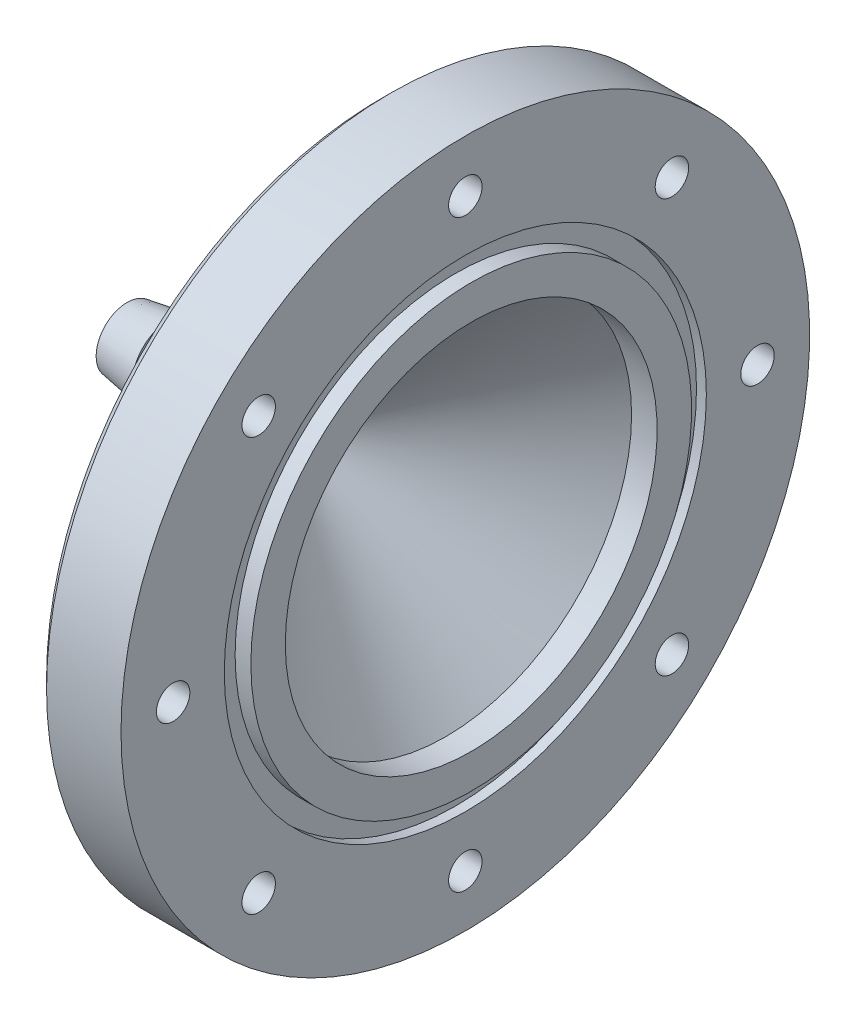
SolidWorks part; units mm, degrees
ref_plane "Front Plane" through (0, 0, 0) normal (0, 0, 1) x (1, 0, 0)
ref_plane "Top Plane" through (0, 0, 0) normal (0, 1, 0) x (1, 0, 0)
ref_plane "Right Plane" through (0, 0, 0) normal (1, 0, 0) x (0, 0, -1)
sketch "Sketch1" plane through (0, 0, 0) normal (0, 0, 1) x (1, 0, 0)
  line L0 (-801.9206, 0) -> (36107.5283, 0) construction
  line L3 (-13.5729, 3.85) -> (-13.5729, 3.15)
  line L8 (-17.9062, 1.9) -> (0, 1.9)
  line L9 (-17.9062, 1.9) -> (-17.9062, 3.15)
  line L10 (16.4699, 24.5) -> (16.4699, 35)
  line L12 (16.4699, 35) -> (7.9039, 35)
  line L16 (16.4699, 24.5) -> (15.4699, 24.5)
  line L17 (15.4699, 24.5) -> (15.4699, 18.9)
  line L18 (7.9039, 35) -> (7.9039, 18.9)
  line L20 (0, 1.9) -> (14.4699, 18.9)
  line L21 (-17.9062, 3.15) -> (-13.5729, 3.85)
  line L22 (14.4699, 18.9) -> (15.4699, 18.9)
  line L23 (-13.5729, 3.15) -> (-9.2395, 3.85)
  line L25 (-9.2395, 3.15) -> (-4.9062, 3.85)
  line L26 (-9.2395, 3.85) -> (-9.2395, 3.15)
  line L27 (-4.9062, 3.85) -> (7.9039, 18.9)
  line L33 (15.4699, 22.4) -> (17.0699, 22.4)
  line L34 (17.0699, 22.4) -> (17.0699, 18.9)
  line L35 (17.0699, 18.9) -> (15.4699, 18.9)
  dimension "D3" = 1
  dimension "D2" = 7.7
  dimension "D6" = 3.8
  dimension "D7" = 6.3
  dimension "D5" = 35
  dimension "D8" = 24.5
  dimension "D4" = 5
  dimension "D9" = 1
  dimension "D11" = 13
  dimension "D12" = 8.566
  dimension "D16" = 3.5
  dimension "D10" = 2.1
  dimension "D13" = 0.6
revolve "Revolve17" add sketch "Sketch1" angle 360 about L0
sketch "Sketch4" plane through (7.9039, 0, 0) normal (-1, 0, 0) x (0, 0, 1)
  line L0 (0, 18.9) -> (0, 35) construction
  circle A0 centre (0, 0) radius 29.7 construction
  circle A1 centre (0, 0) radius 18.9 construction
  circle A2 centre (0, 0) radius 35 construction
  point P3 (0, 29.7)
  point P7 (29.7, 0)
  point P12 (-29.7, 0)
  point P13 (0, -29.7)
  point P22 (-21.0011, 20.8472)
  point P25 (21.0011, 20.8472)
  point P28 (21.0011, -21.1549)
  point P31 (-21.0011, -21.1549)
  dimension "D1" = 5.3
  dimension "D2" = 5.3
hole_wizard "CBORE for M3 Hex Socket Head Cap Screw2" positions "Sketch4" profile "Sketch5" counterbore size "M3" standard "ISO"
sketch "Sketch5" plane through (7.9039, -21.1549, -21.0011) normal (0, 1, 0) x (0, 0, 1)
  line L0 (0, 0) -> (0, 9.5875)
  line L1 (0, 9.5875) -> (1.7, 8.566)
  line L2 (1.7, 8.566) -> (1.7, 3.4)
  line L3 (1.7, 3.4) -> (3.25, 3.4)
  line L4 (3.25, 3.4) -> (3.25, 0)
  line L5 (3.25, 0) -> (0, 0)
  line L10 (0, 9.5875) -> (-1.7, 8.566) construction
  line L11 (0, -6.35) -> (0, 107.95) construction
  dimension "Hole Dia." = 3.4
  dimension "Hole Depth" = 8.566
  dimension "C'Bore Dia." = 6.5
  dimension "C'Bore Depth" = 3.4
  dimension "Drill Angle" = 118
chamfer "Chamfer1" distance 1 angle 45 1 edges at (7.9039, 0, 35)
sketch "Sketch6" plane through (16.4699, 0, 0) normal (1, 0, 0) x (0, 0, -1)
  line L0 (0, 35) -> (0, 24.5)
  circle A0 centre (0, 0) radius 35
  circle A1 centre (0, 0) radius 35 construction
  circle A2 centre (0, 0) radius 24.5 construction
equation "\"D9@Sketch1\"=\"D3@Sketch1\""
